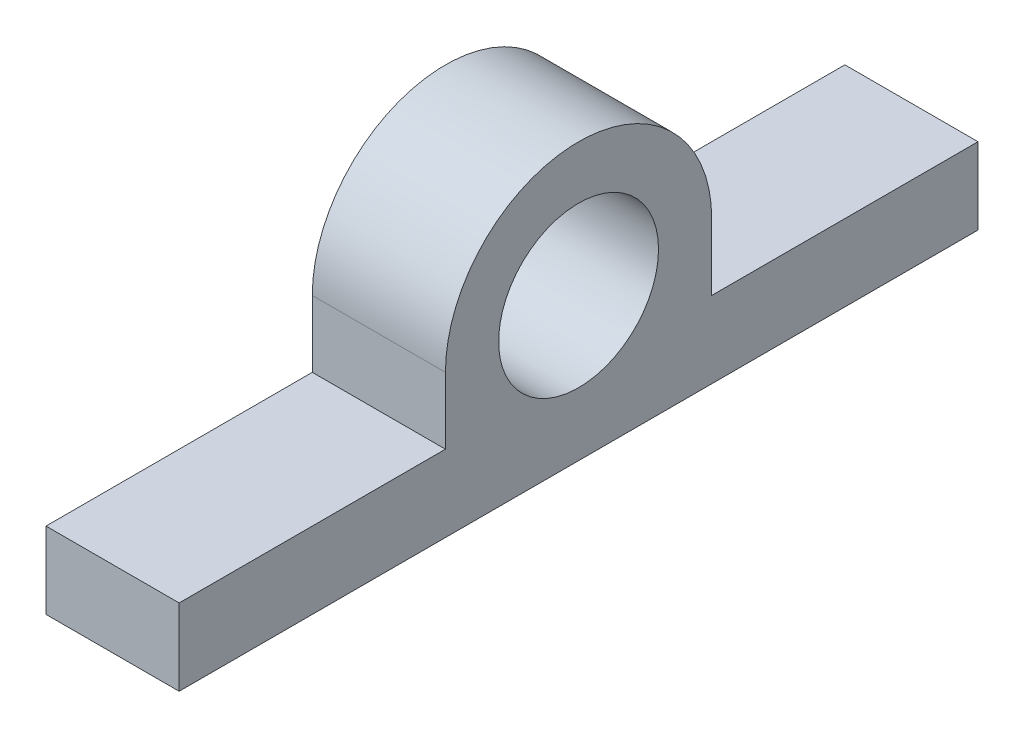
SolidWorks part; units mm, degrees
ref_plane "Front Plane" through (0, 0, 0) normal (0, 0, 1) x (1, 0, 0)
ref_plane "Top Plane" through (0, 0, 0) normal (0, 1, 0) x (1, 0, 0)
ref_plane "Right Plane" through (0, 0, 0) normal (1, 0, 0) x (0, 0, -1)
sketch "Sketch1" plane through (0, 0, 0) normal (1, 0, 0) x (0, 0, -1)
  line L0 (0, 0) -> (76.2, 0)
  line L1 (76.2, 0) -> (76.2, 7.3)
  line L2 (76.2, 7.3) -> (50.8, 7.3)
  line L3 (0, 7.3) -> (0, 0)
  line L5 (50.8, 7.3) -> (50.8, 13.65)
  line L7 (25.4, 13.65) -> (25.4, 7.3)
  line L9 (25.4, 7.3) -> (0, 7.3)
  arc A0 (50.8, 13.65) -> (25.4, 13.65) centre (38.1, 13.65) ccw
  dimension "D1" = 76.2
  dimension "D2" = 7.3
  dimension "D3" = 25.4
  dimension "D4" = 25.4
  dimension "D5" = 6.35
extrude "Boss-Extrude1" add sketch "Sketch1" along normal blind 12.7
sketch "Sketch2" plane through (12.7, 0, 0) normal (1, 0, 0) x (0, 0, -1)
  circle A0 centre (38.1, 13.65) radius 7.625
  dimension "D1" = 15.25
extrude "Cut-Extrude1" cut sketch "Sketch2" against normal through all
sketch "Sketch3" plane through (0, 0, 0) normal (0, -1, 0) x (1, 0, 0)
  line L0 (12.7, -76.2) -> (0, -76.2) construction
  line L3 (12.7, 0) -> (0, 0) construction
  circle A0 centre (6.35, -12.7) radius 2
  circle A1 centre (6.35, -63.5) radius 2
  point P4 (6.35, 0)
  point P10 (6.35, -76.2)
  dimension "D1" = 4
  dimension "D4" = 4
  dimension "D6" = 12.7
  dimension "D2" = 0
  dimension "D3" = 12.7
  dimension "D5" = 0
  dimension "D7" = 50.8
extrude "Cut-Extrude2" cut sketch "Sketch3" against normal blind 7
equation "\"bearing_d\"= 0.5in"
equation "\"heat_set_d\"= 0.1in"
